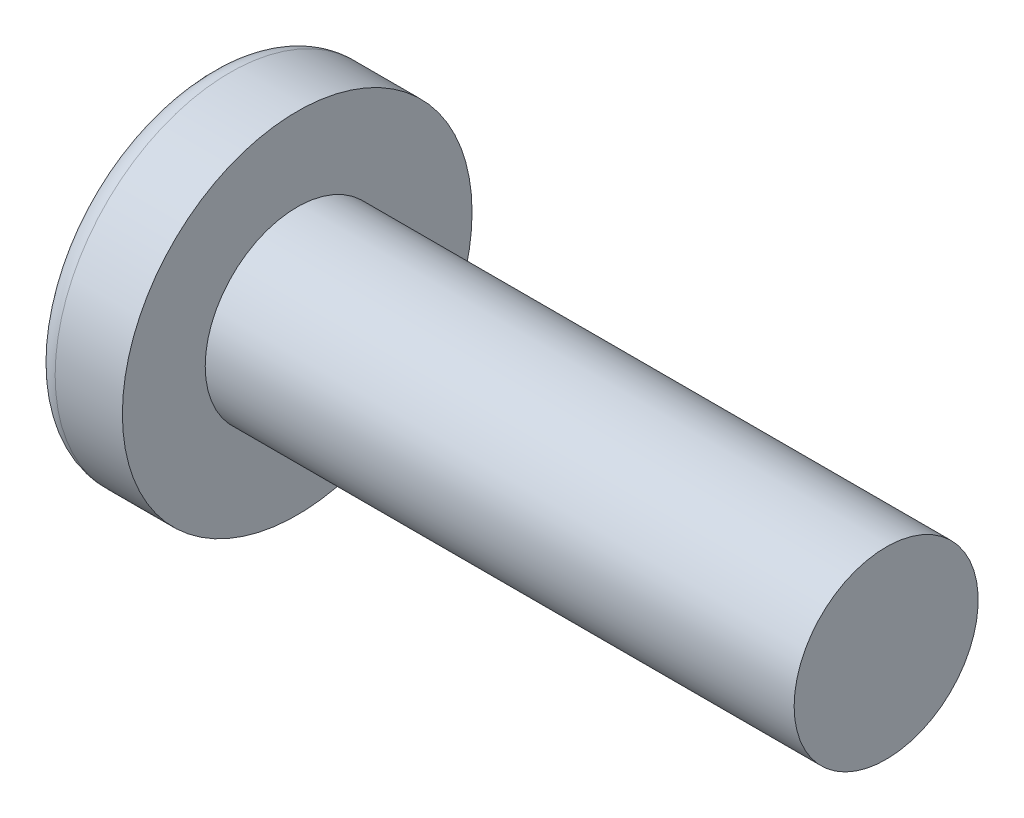
SolidWorks part; units mm, degrees
ref_plane "Plane1" through (0, 0, 0) normal (0, 0, 1) x (1, 0, 0)
ref_plane "Plane2" through (0, 0, 0) normal (0, 1, 0) x (1, 0, 0)
ref_plane "Plane3" through (0, 0, 0) normal (1, 0, 0) x (0, 0, -1)
sketch "BodySke" plane through (0, 0, 0) normal (0, 0, 1) x (1, 0, 0)
  line L0 (3.7, 2.5) -> (3.7, 4.75)
  line L1 (4.5, 6.35) -> (4.5, -3.175) construction
  line L2 (-25.4, 0) -> (127, 0) construction
  line L3 (19.7, 0) -> (0, 0)
  line L4 (3.7, 2.5) -> (19.7, 2.5)
  line L5 (19.7, 2.5) -> (19.7, 0)
  line L6 (1.8732, 4.75) -> (3.7, 4.75)
  line L7 (3.7, -2.5) -> (19.7, -2.5) construction
  line L8 (3.7, 6.35) -> (3.7, -3.175) construction
  arc A0 (1.3764, 4.4865) -> (0, 0) centre (8, 0) ccw
  arc A2 (1.3764, 4.4865) -> (1.8732, 4.75) centre (1.8732, 4.15) cw
  dimension "Head_crown_rad" = 8
  dimension "Head_fillet_rad" = 0.6
  dimension "Diameter" = 5
  dimension "Length" = 16
  dimension "Head_ht" = 3.7
  dimension "Head_dia" = 9.5
  dimension "Advance" = 0.8
  dimension "Thread_nom" = 16
revolve "Base-Revolve" add sketch "BodySke" angle 360 about L2
cosmetic thread "ThreadCosmetic" [suppressed] parameters "Thread_length"=15.2, "Thread_minor"=4.11
sketch "Sketch3" plane through (0, 0, 0) normal (1, 0, 0) x (0, 0, -1)
  line L0 (0.5, -2.45) -> (-0.5, -2.45)
  line L1 (0.5, -2.45) -> (0.5, 2.45)
  line L2 (-0.5, 2.45) -> (0.5, 2.45)
  line L3 (-0.5, 2.45) -> (-0.5, -2.45)
  dimension "Cross_dia" = 4.9
  dimension "D1" = 2.45
  dimension "Cross_width" = 1
  dimension "D2" = 0.5
ref_plane "Plane4" through (2.95, 0, 0) normal (1, 0, 0) x (0, 0, -1)
sketch "Sketch4" plane through (2.95, 0, 0) normal (1, 0, 0) x (0, 0, -1)
  line L0 (0.25, -0.25) -> (-0.25, -0.25)
  line L1 (0.25, -0.25) -> (0.25, 0.25)
  line L2 (-0.25, 0.25) -> (0.25, 0.25)
  line L3 (-0.25, 0.25) -> (-0.25, -0.25)
  dimension "D2" = 0.5
  dimension "D1" = 0.5
  dimension "D3" = 0.25
  dimension "D4" = 0.25
loft "Cut-Loft1" cut profiles "Sketch3", "Sketch4"
pattern_circular "CirPattern1" count 2 every 90 about axis through (0, 0, 0) along (1, 0, 0) of "Cut-Loft1"
sketch "ThdSchSke" plane through (0, 0, 0) normal (0, 0, 1) x (1, 0, 0)
  line L0 (4.5, -2.055) -> (4.1884, -2.5)
  line L1 (4.5, -2.055) -> (4.8116, -2.5)
  line L2 (4.8116, -2.5) -> (4.8116, -3.125)
  line L3 (-3.175, 0) -> (5.1513, 0) construction
  line L5 (4.8116, -3.125) -> (4.1884, -3.125)
  line L6 (4.1884, -3.125) -> (4.1884, -2.5)
  dimension "Diameter" = 5
  dimension "SideAngle" = 55
  dimension "VeeAngle" = 70
  dimension "Thread_minor" = 4.11
  dimension "Overcut" = 6.25
  dimension "Start" = 4.5
revolve "ThreadSchematic" [suppressed] cut sketch "ThdSchSke" angle 360 about L3
pattern_linear "ThdSchPat" [suppressed]
equation "\"D1@Sketch3\" = \"Cross_dia@Sketch3\" / 2"
equation "\"D2@Sketch3\" = \"Cross_width@Sketch3\" / 2"
equation "\"D1@Sketch4\" = \"Cross_width@Sketch3\" *.5"
equation "\"D2@Sketch4\" = \"D1@Sketch4\""
equation "\"D3@Sketch4\" = \"D1@Sketch4\" / 2"
equation "\"D4@Sketch4\" = \"D2@Sketch4\" / 2"
equation "\"Thread_length@ThreadCosmetic\" = ((sgn( (\"Length@BodySke\" - \"Advance@BodySke\" ) - \"Thread_nom@BodySke\" )-1)*( (\"Length@BodySke\" - \"Advance@BodySke\" ) - \"Thread_nom@BodySke\" ))/-2+ \"Thread_nom@BodySke\""
equation "\"Thread_minor@ThdSchSke\" = \"Thread_minor@ThreadCosmetic\""
equation "\"Diameter@ThdSchSke\" = \"Diameter@BodySke\""
equation "\"Overcut@ThdSchSke\" = \"Diameter@BodySke\" * 1.25"
equation "\"Start@ThdSchSke\" = \"Head_ht@BodySke\" + \"Length@BodySke\" - \"Thread_length@ThreadCosmetic\"  '---Non-countersunk---"
equation "\"Num_threads@ThdSchPat\" = int( \"Thread_length@ThreadCosmetic\" / \"Advance@BodySke\" + 0.999 )  + 1"
equation "\"Advance@ThdSchPat\" = \"Thread_length@ThreadCosmetic\" /  (\"Num_threads@ThdSchPat\" - 1) 'relax it"
